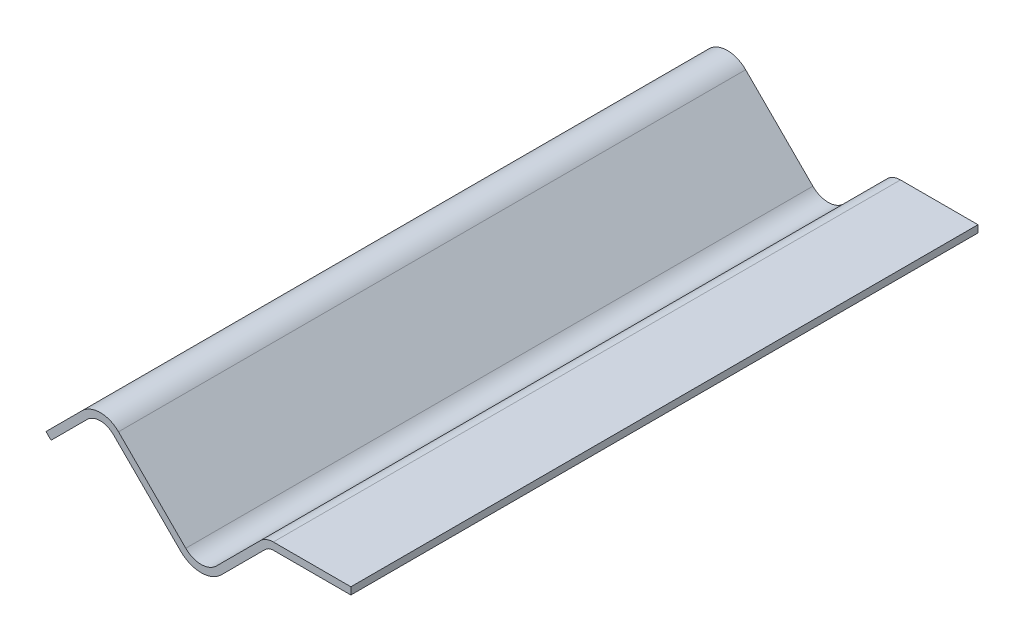
SolidWorks part; units mm, degrees
material "Stainless Steel (ferritic)"
ref_plane "Front Plane" through (0, 0, 0) normal (0, 0, 1) x (1, 0, 0)
ref_plane "Top Plane" through (0, 0, 0) normal (0, 1, 0) x (1, 0, 0)
ref_plane "Right Plane" through (0, 0, 0) normal (1, 0, 0) x (0, 0, -1)
sketch "Sketch2" plane through (0, 0, 0) normal (0, 0, 1) x (1, 0, 0)
  line L0 (0, 0) -> (14.5878, 14.5878)
  line L1 (29.3705, 14.5878) -> (56.6055, -12.6473)
  line L2 (69.0312, -12.6473) -> (86.7622, 5.0838)
  line L3 (92.0805, 7.2867) -> (123.4845, 7.2867)
  line L4 (123.4845, 7.2867) -> (123.4845, 4.3845)
  line L5 (123.4845, 4.3845) -> (92.0805, 4.3845)
  line L6 (88.8144, 3.0316) -> (71.0833, -14.6994)
  line L7 (54.5533, -14.6994) -> (27.3183, 12.5356)
  line L8 (16.6399, 12.5356) -> (2.0522, -2.0522)
  line L9 (2.0522, -2.0522) -> (0, 0)
  arc A0 (14.5878, 14.5878) -> (29.3705, 14.5878) centre (21.9791, 7.1964) cw
  arc A1 (56.6055, -12.6473) -> (69.0312, -12.6473) centre (62.8183, -6.4344) ccw
  arc A2 (86.7622, 5.0838) -> (92.0805, 7.2867) centre (92.0805, -0.2345) cw
  arc A3 (92.0805, 4.3845) -> (88.8144, 3.0316) centre (92.0805, -0.2345) ccw
  arc A4 (71.0833, -14.6994) -> (54.5533, -14.6994) centre (62.8183, -6.4344) cw
  arc A5 (27.3183, 12.5356) -> (16.6399, 12.5356) centre (21.9791, 7.1964) ccw
  point P3 (0, 0)
  point P22 (0, 0)
extrude "Boss-Extrude1" add sketch "Sketch2" along normal mid plane 254
